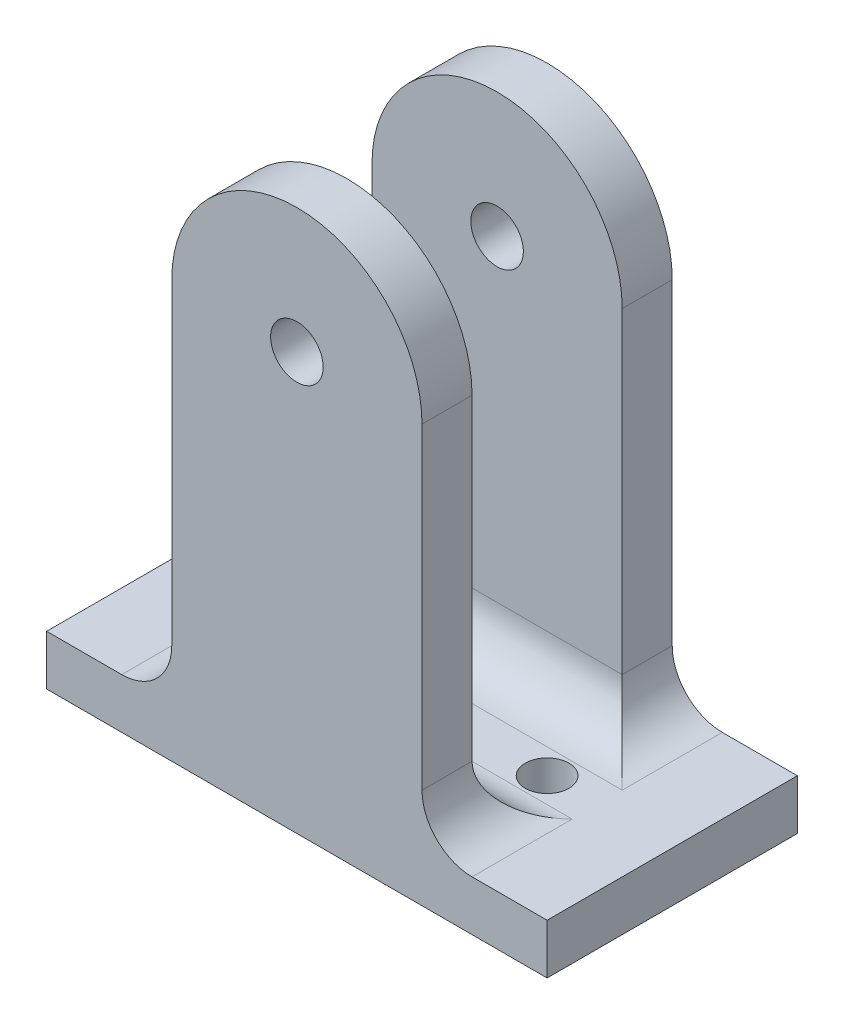
SolidWorks part; units mm, degrees
material "Custom Plastic"
ref_plane "Front Plane" through (0, 0, 0) normal (0, 0, 1) x (1, 0, 0)
ref_plane "Top Plane" through (0, 0, 0) normal (0, 1, 0) x (1, 0, 0)
ref_plane "Right Plane" through (0, 0, 0) normal (1, 0, 0) x (0, 0, -1)
sketch "Sketch1" plane through (0, 0, 0) normal (0, 1, 0) x (1, 0, 0)
  line L0 (0, 19.05) -> (76.2, 19.05) construction
  line L1 (0, 0) -> (76.2, 0)
  line L2 (0, 0) -> (0, 38.1)
  line L3 (0, 38.1) -> (76.2, 38.1)
  line L4 (76.2, 0) -> (76.2, 38.1)
  line L5 (38.1, 38.1) -> (38.1, 0) construction
  circle A0 centre (19.05, 19.05) radius 3.3274
  circle A1 centre (57.15, 19.05) radius 3.3274
  dimension "D3" = 6.6548
  dimension "D1" = 76.2
  dimension "D2" = 38.1
  dimension "D4" = 19.05
extrude "Boss-Extrude1" add sketch "Sketch1" along normal blind 7.62
ref_plane "Plane1" through (0, 0, -19.05) normal (0, 0, 1) x (1, 0, 0)
sketch "Sketch2" plane through (0, 0, 0) normal (0, 0, 1) x (1, 0, 0)
  line L3 (0, 0) -> (76.2, 0) construction
  line L5 (19.05, 0) -> (19.05, 63.5)
  line L7 (57.15, 0) -> (57.15, 63.5)
  line L8 (19.05, 0) -> (57.15, 0)
  line L9 (0, 7.62) -> (0, 0) construction
  arc A2 (19.05, 63.5) -> (57.15, 63.5) centre (38.1, 63.5) cw
  circle A3 centre (38.1, 63.5) radius 4
  dimension "D2" = 19.05
  dimension "D3" = 19.05
  dimension "D4" = 8
  dimension "D1" = 63.5
extrude "Boss-Extrude2" add sketch "Sketch2" against normal blind 7.62
fillet "Fillet1" radius 7.62 3 edges at (38.1, 7.62, -7.62) (19.05, 7.62, -3.81) (57.15, 7.62, -3.81)
mirror "Mirror2" about plane through (0, 0, -19.05) normal (0, 0, 1) of "Boss-Extrude2", "Fillet1"
